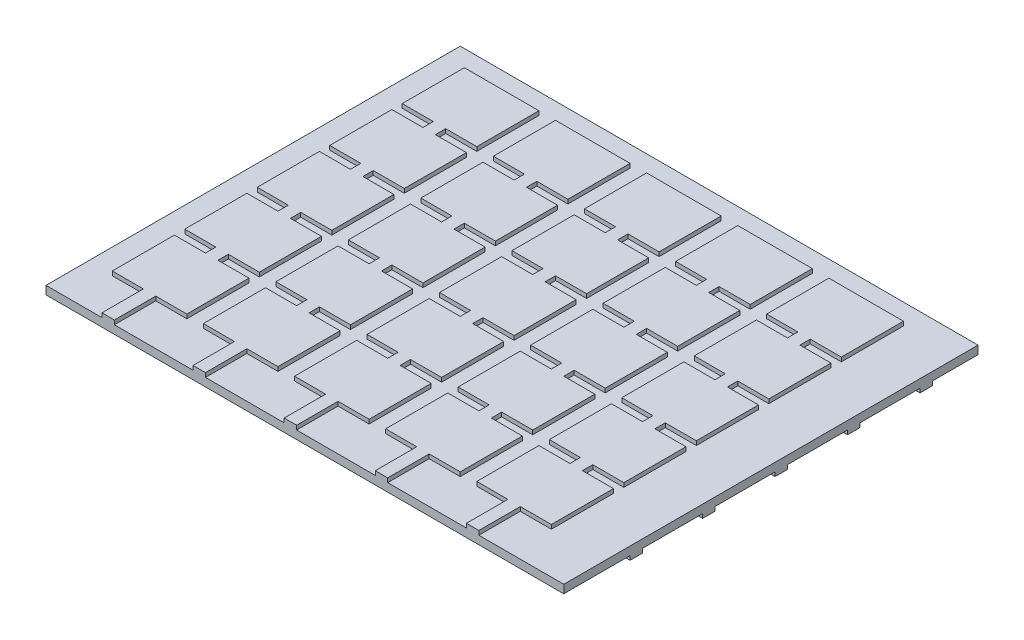
SolidWorks part; units mm, degrees
ref_plane "Front Plane" through (0, 0, 0) normal (0, 0, 1) x (1, 0, 0)
ref_plane "Top Plane" through (0, 0, 0) normal (0, 1, 0) x (1, 0, 0)
ref_plane "Right Plane" through (0, 0, 0) normal (1, 0, 0) x (0, 0, -1)
sketch "Sketch1" plane through (0, 0, 0) normal (0, 1, 0) x (1, 0, 0)
  line L1 (-62.5, 50) -> (62.5, 50)
  line L2 (-62.5, 50) -> (-62.5, -50)
  line L3 (-62.5, -50) -> (62.5, -50)
  line L4 (62.5, 50) -> (62.5, -50)
  dimension "D1" = 100
  dimension "D2" = 125
  dimension "D3" = 62.5
  dimension "D4" = 50
extrude "Boss-Extrude1" add sketch "Sketch1" along normal blind 2
sketch "Sketch2" plane through (0, 2, 0) normal (0, 1, 0) x (1, 0, 0)
  line L0 (62.5, 50) -> (-62.5, 50) construction
  line L1 (-56.5, 45) -> (-38.5, 45)
  line L2 (-56.5, 45) -> (-56.5, 30)
  line L3 (-56.5, 30) -> (-49, 30)
  line L4 (-38.5, 45) -> (-38.5, 30)
  line L5 (-62.5, 50) -> (-62.5, -50) construction
  line L6 (-34.5, 45) -> (-34.5, 30)
  line L7 (-34.5, 45) -> (-16.5, 45)
  line L8 (-16.5, 45) -> (-16.5, 30)
  line L9 (-34.5, 30) -> (-27, 30)
  line L10 (-12.5, 45) -> (-12.5, 30)
  line L11 (-12.5, 45) -> (5.5, 45)
  line L12 (5.5, 45) -> (5.5, 30)
  line L13 (-12.5, 30) -> (-5, 30)
  line L14 (9.5, 45) -> (9.5, 30)
  line L15 (9.5, 45) -> (27.5, 45)
  line L16 (27.5, 45) -> (27.5, 30)
  line L17 (9.5, 30) -> (17, 30)
  line L18 (31.5, 45) -> (31.5, 30)
  line L19 (31.5, 45) -> (49.5, 45)
  line L20 (49.5, 45) -> (49.5, 30)
  line L21 (31.5, 30) -> (39, 30)
  line L22 (-34.5, 27.5) -> (-34.5, 12.5)
  line L23 (-34.5, 27.5) -> (-27, 27.5)
  line L24 (-16.5, 27.5) -> (-16.5, 12.5)
  line L25 (-34.5, 12.5) -> (-27, 12.5)
  line L26 (-12.5, 27.5) -> (-12.5, 12.5)
  line L27 (-12.5, 27.5) -> (-5, 27.5)
  line L28 (5.5, 27.5) -> (5.5, 12.5)
  line L29 (-12.5, 12.5) -> (-5, 12.5)
  line L30 (9.5, 27.5) -> (9.5, 12.5)
  line L31 (9.5, 27.5) -> (17, 27.5)
  line L32 (27.5, 27.5) -> (27.5, 12.5)
  line L33 (9.5, 12.5) -> (17, 12.5)
  line L34 (31.5, 27.5) -> (31.5, 12.5)
  line L35 (31.5, 27.5) -> (39, 27.5)
  line L36 (49.5, 27.5) -> (49.5, 12.5)
  line L37 (31.5, 12.5) -> (39, 12.5)
  line L38 (-34.5, 10) -> (-34.5, -5)
  line L39 (-34.5, 10) -> (-27, 10)
  line L40 (-16.5, 10) -> (-16.5, -5)
  line L41 (-34.5, -5) -> (-27, -5)
  line L42 (-12.5, 10) -> (-12.5, -5)
  line L43 (-12.5, 10) -> (-5, 10)
  line L44 (5.5, 10) -> (5.5, -5)
  line L45 (-12.5, -5) -> (-5, -5)
  line L46 (9.5, 10) -> (9.5, -5)
  line L47 (9.5, 10) -> (17, 10)
  line L48 (27.5, 10) -> (27.5, -5)
  line L49 (9.5, -5) -> (17, -5)
  line L50 (31.5, 10) -> (31.5, -5)
  line L51 (31.5, 10) -> (39, 10)
  line L52 (49.5, 10) -> (49.5, -5)
  line L53 (31.5, -5) -> (39, -5)
  line L54 (-34.5, -7.5) -> (-34.5, -22.5)
  line L55 (-34.5, -7.5) -> (-27, -7.5)
  line L56 (-16.5, -7.5) -> (-16.5, -22.5)
  line L57 (-34.5, -22.5) -> (-27, -22.5)
  line L58 (-12.5, -7.5) -> (-12.5, -22.5)
  line L59 (-12.5, -7.5) -> (-5, -7.5)
  line L60 (5.5, -7.5) -> (5.5, -22.5)
  line L61 (-12.5, -22.5) -> (-5, -22.5)
  line L62 (9.5, -7.5) -> (9.5, -22.5)
  line L63 (9.5, -7.5) -> (17, -7.5)
  line L64 (27.5, -7.5) -> (27.5, -22.5)
  line L65 (9.5, -22.5) -> (17, -22.5)
  line L66 (31.5, -7.5) -> (31.5, -22.5)
  line L67 (31.5, -7.5) -> (39, -7.5)
  line L68 (49.5, -7.5) -> (49.5, -22.5)
  line L69 (31.5, -22.5) -> (39, -22.5)
  line L70 (-34.5, -25) -> (-34.5, -40)
  line L71 (-34.5, -25) -> (-27, -25)
  line L72 (-16.5, -25) -> (-16.5, -40)
  line L73 (-34.5, -40) -> (-27, -40)
  line L74 (-12.5, -25) -> (-12.5, -40)
  line L75 (-12.5, -25) -> (-5, -25)
  line L76 (5.5, -25) -> (5.5, -40)
  line L77 (-12.5, -40) -> (-5, -40)
  line L78 (9.5, -25) -> (9.5, -40)
  line L79 (9.5, -25) -> (17, -25)
  line L80 (27.5, -25) -> (27.5, -40)
  line L81 (9.5, -40) -> (17, -40)
  line L82 (31.5, -25) -> (31.5, -40)
  line L83 (31.5, -25) -> (39, -25)
  line L84 (49.5, -25) -> (49.5, -40)
  line L85 (31.5, -40) -> (39, -40)
  line L86 (-56.5, 27.5) -> (-56.5, 12.5)
  line L87 (-56.5, 27.5) -> (-49, 27.5)
  line L88 (-38.5, 27.5) -> (-38.5, 12.5)
  line L89 (-56.5, 12.5) -> (-49, 12.5)
  line L90 (-56.5, 10) -> (-56.5, -5)
  line L91 (-56.5, 10) -> (-49, 10)
  line L92 (-38.5, 10) -> (-38.5, -5)
  line L93 (-56.5, -5) -> (-49, -5)
  line L94 (-56.5, -7.5) -> (-56.5, -22.5)
  line L95 (-56.5, -7.5) -> (-49, -7.5)
  line L96 (-38.5, -7.5) -> (-38.5, -22.5)
  line L97 (-56.5, -22.5) -> (-49, -22.5)
  line L98 (-56.5, -25) -> (-56.5, -40)
  line L99 (-56.5, -25) -> (-49, -25)
  line L100 (-38.5, -25) -> (-38.5, -40)
  line L101 (-56.5, -40) -> (-49, -40)
  line L102 (-62.5, -50) -> (62.5, -50) construction
  line L103 (-46, 30) -> (-38.5, 30)
  line L104 (-49, 30) -> (-49, 27.5)
  line L105 (-49, -50) -> (-46, -50)
  line L106 (-46, 30) -> (-46, 27.5)
  line L107 (-46, 27.5) -> (-38.5, 27.5)
  line L108 (-24, 30) -> (-16.5, 30)
  line L109 (-27, 30) -> (-27, 27.5)
  line L110 (-27, -50) -> (-24, -50)
  line L111 (-24, 30) -> (-24, 27.5)
  line L112 (-2, 30) -> (5.5, 30)
  line L113 (-5, 30) -> (-5, 27.5)
  line L114 (-5, -50) -> (-2, -50)
  line L115 (-2, 30) -> (-2, 27.5)
  line L116 (42, 30) -> (49.5, 30)
  line L117 (17, 30) -> (17, 27.5)
  line L118 (17, -50) -> (20, -50)
  line L119 (20, 30) -> (20, 27.5)
  line L121 (39, 30) -> (39, 27.5)
  line L122 (39, -50) -> (42, -50)
  line L123 (42, 30) -> (42, 27.5)
  line L124 (-46, 12.5) -> (-46, 10)
  line L125 (-49, 12.5) -> (-49, 10)
  line L126 (-46, 12.5) -> (-38.5, 12.5)
  line L127 (-46, 10) -> (-38.5, 10)
  line L128 (-49, -5) -> (-49, -7.5)
  line L129 (-46, -5) -> (-46, -7.5)
  line L130 (-46, -5) -> (-38.5, -5)
  line L131 (-46, -7.5) -> (-38.5, -7.5)
  line L132 (-49, -22.5) -> (-49, -25)
  line L133 (-46, -22.5) -> (-46, -25)
  line L134 (-46, -22.5) -> (-38.5, -22.5)
  line L135 (-46, -25) -> (-38.5, -25)
  line L136 (-49, -40) -> (-49, -50)
  line L137 (-46, -40) -> (-46, -50)
  line L138 (-46, -40) -> (-38.5, -40)
  line L139 (-24, -40) -> (-24, -50)
  line L140 (-27, -40) -> (-27, -50)
  line L141 (-24, -40) -> (-16.5, -40)
  line L142 (-24, -25) -> (-16.5, -25)
  line L143 (-24, -22.5) -> (-16.5, -22.5)
  line L144 (-24, -22.5) -> (-24, -25)
  line L145 (-27, -22.5) -> (-27, -25)
  line L146 (-24, -5) -> (-24, -7.5)
  line L147 (-27, -5) -> (-27, -7.5)
  line L148 (-24, -5) -> (-16.5, -5)
  line L149 (-24, -7.5) -> (-16.5, -7.5)
  line L150 (-24, 10) -> (-16.5, 10)
  line L151 (-24, 12.5) -> (-16.5, 12.5)
  line L152 (-27, 12.5) -> (-27, 10)
  line L153 (-24, 12.5) -> (-24, 10)
  line L154 (-24, 27.5) -> (-16.5, 27.5)
  line L155 (-2, 27.5) -> (5.5, 27.5)
  line L156 (-5, 12.5) -> (-5, 10)
  line L157 (-2, 12.5) -> (-2, 10)
  line L158 (-2, 12.5) -> (5.5, 12.5)
  line L159 (-2, 10) -> (5.5, 10)
  line L160 (-5, -5) -> (-5, -7.5)
  line L161 (-2, -5) -> (-2, -7.5)
  line L162 (-2, -5) -> (5.5, -5)
  line L163 (-2, -7.5) -> (5.5, -7.5)
  line L164 (-5, -22.5) -> (-5, -25)
  line L165 (-2, -22.5) -> (-2, -25)
  line L166 (-2, -22.5) -> (5.5, -22.5)
  line L167 (-2, -25) -> (5.5, -25)
  line L168 (-5, -40) -> (-5, -50)
  line L169 (-2, -40) -> (-2, -50)
  line L170 (-2, -40) -> (5.5, -40)
  line L171 (20, -40) -> (20, -50)
  line L172 (17, -40) -> (17, -50)
  line L173 (20, -40) -> (27.5, -40)
  line L174 (20, -22.5) -> (20, -25)
  line L175 (17, -22.5) -> (17, -25)
  line L176 (20, -22.5) -> (27.5, -22.5)
  line L177 (20, -25) -> (27.5, -25)
  line L178 (20, -5) -> (20, -7.5)
  line L179 (17, -5) -> (17, -7.5)
  line L180 (20, -5) -> (27.5, -5)
  line L181 (20, -7.5) -> (27.5, -7.5)
  line L182 (20, 12.5) -> (20, 10)
  line L183 (17, 12.5) -> (17, 10)
  line L184 (20, 12.5) -> (27.5, 12.5)
  line L185 (20, 10) -> (27.5, 10)
  line L186 (20, 30) -> (27.5, 30)
  line L187 (20, 27.5) -> (27.5, 27.5)
  line L188 (42, 27.5) -> (49.5, 27.5)
  line L189 (42, 12.5) -> (42, 10)
  line L190 (39, 12.5) -> (39, 10)
  line L191 (42, 12.5) -> (49.5, 12.5)
  line L192 (42, 10) -> (49.5, 10)
  line L193 (39, -5) -> (39, -7.5)
  line L194 (42, -5) -> (42, -7.5)
  line L195 (42, -5) -> (49.5, -5)
  line L196 (42, -7.5) -> (49.5, -7.5)
  line L197 (39, -22.5) -> (39, -25)
  line L198 (42, -22.5) -> (42, -25)
  line L199 (42, -22.5) -> (49.5, -22.5)
  line L200 (42, -25) -> (49.5, -25)
  line L201 (39, -40) -> (39, -50)
  line L202 (42, -40) -> (42, -50)
  line L203 (42, -40) -> (49.5, -40)
  dimension "D1" = 5
  dimension "D2" = 6
  dimension "D3" = 18
  dimension "D4" = 15
  dimension "D8" = 7.5
  dimension "D9" = 7.5
  dimension "D10" = 22
  dimension "D12" = 7.5
  dimension "D14" = 7.5
  dimension "D16" = 7.5
  dimension "D5" = 5
  dimension "D6" = 5
extrude "Boss-Extrude2" add sketch "Sketch2" along normal blind 1
sketch "Sketch3" plane through (0, 0, 0) normal (0, -1, 0) x (1, 0, 0)
  line L0 (-38.5, 40) -> (-38.5, 34)
  line L1 (-56.5, 40) -> (-38.5, 40)
  line L2 (-56.5, 40) -> (-56.5, 25)
  line L3 (-56.5, -45) -> (-38.5, -45)
  line L4 (49.5, 40) -> (49.5, 34)
  line L5 (-34.5, 40) -> (-34.5, 34)
  line L6 (-16.5, 40) -> (-16.5, 34)
  line L7 (9.5, 40) -> (9.5, 34)
  line L8 (-12.5, 40) -> (-12.5, 34)
  line L9 (5.5, 40) -> (5.5, 34)
  line L10 (27.5, 40) -> (27.5, 34)
  line L11 (31.5, 40) -> (31.5, 34)
  line L12 (-56.5, 25) -> (-38.5, 25)
  line L13 (-56.5, 22.5) -> (-38.5, 22.5)
  line L14 (49.5, 7.5) -> (31.5, 7.5)
  line L15 (-56.5, 5) -> (-38.5, 5)
  line L16 (-56.5, -10) -> (-38.5, -10)
  line L17 (49.5, -12.5) -> (31.5, -12.5)
  line L18 (-56.5, -27.5) -> (-38.5, -27.5)
  line L19 (49.5, -30) -> (31.5, -30)
  line L20 (-56.5, -30) -> (-56.5, -45)
  line L21 (-38.5, -30) -> (-38.5, -36)
  line L22 (-34.5, -30) -> (-34.5, -36)
  line L23 (-34.5, -27.5) -> (-16.5, -27.5)
  line L24 (-38.5, -30) -> (-56.5, -30)
  line L25 (-12.5, -27.5) -> (5.5, -27.5)
  line L26 (-16.5, -30) -> (-34.5, -30)
  line L27 (-16.5, -30) -> (-16.5, -36)
  line L28 (-12.5, -30) -> (-12.5, -36)
  line L29 (9.5, -27.5) -> (27.5, -27.5)
  line L30 (5.5, -30) -> (-12.5, -30)
  line L31 (9.5, -30) -> (9.5, -36)
  line L32 (5.5, -30) -> (5.5, -36)
  line L33 (27.5, -30) -> (27.5, -36)
  line L34 (31.5, -30) -> (31.5, -36)
  line L35 (31.5, -27.5) -> (49.5, -27.5)
  line L36 (27.5, -30) -> (9.5, -30)
  line L37 (49.5, -30) -> (49.5, -36)
  line L38 (31.5, -10) -> (49.5, -10)
  line L39 (27.5, -12.5) -> (9.5, -12.5)
  line L40 (27.5, -12.5) -> (27.5, -18.5)
  line L41 (31.5, -12.5) -> (31.5, -18.5)
  line L42 (49.5, -12.5) -> (49.5, -18.5)
  line L43 (49.5, 5) -> (49.5, -1)
  line L44 (31.5, 5) -> (31.5, -1)
  line L45 (27.5, 5) -> (27.5, -1)
  line L46 (27.5, 7.5) -> (9.5, 7.5)
  line L47 (31.5, 5) -> (49.5, 5)
  line L48 (31.5, 22.5) -> (49.5, 22.5)
  line L49 (31.5, 25) -> (49.5, 25)
  line L50 (27.5, 22.5) -> (27.5, 16.5)
  line L51 (31.5, 22.5) -> (31.5, 16.5)
  line L52 (49.5, 22.5) -> (49.5, 16.5)
  line L53 (31.5, 40) -> (49.5, 40)
  line L54 (9.5, 40) -> (27.5, 40)
  line L55 (9.5, 25) -> (27.5, 25)
  line L56 (9.5, 22.5) -> (27.5, 22.5)
  line L57 (5.5, 22.5) -> (5.5, 16.5)
  line L58 (9.5, 22.5) -> (9.5, 16.5)
  line L59 (5.5, 7.5) -> (-12.5, 7.5)
  line L60 (9.5, 5) -> (27.5, 5)
  line L61 (5.5, 5) -> (5.5, -1)
  line L62 (9.5, 5) -> (9.5, -1)
  line L63 (9.5, -10) -> (27.5, -10)
  line L64 (5.5, -12.5) -> (-12.5, -12.5)
  line L65 (5.5, -12.5) -> (5.5, -18.5)
  line L66 (9.5, -12.5) -> (9.5, -18.5)
  line L67 (-12.5, -10) -> (5.5, -10)
  line L68 (-16.5, -12.5) -> (-34.5, -12.5)
  line L69 (-16.5, -12.5) -> (-16.5, -18.5)
  line L70 (-12.5, -12.5) -> (-12.5, -18.5)
  line L71 (-16.5, 7.5) -> (-34.5, 7.5)
  line L72 (-12.5, 5) -> (5.5, 5)
  line L73 (-16.5, 5) -> (-16.5, -1)
  line L74 (-12.5, 5) -> (-12.5, -1)
  line L75 (-12.5, 25) -> (5.5, 25)
  line L76 (-12.5, 22.5) -> (5.5, 22.5)
  line L77 (-16.5, 22.5) -> (-16.5, 16.5)
  line L78 (-12.5, 22.5) -> (-12.5, 16.5)
  line L79 (-12.5, 40) -> (5.5, 40)
  line L80 (-34.5, 40) -> (-16.5, 40)
  line L81 (-34.5, 25) -> (-16.5, 25)
  line L82 (-34.5, 22.5) -> (-16.5, 22.5)
  line L83 (-38.5, 22.5) -> (-38.5, 16.5)
  line L84 (-34.5, 22.5) -> (-34.5, 16.5)
  line L85 (-38.5, 7.5) -> (-56.5, 7.5)
  line L86 (-34.5, 5) -> (-16.5, 5)
  line L87 (-38.5, 5) -> (-38.5, -1)
  line L88 (-34.5, 5) -> (-34.5, -1)
  line L89 (-34.5, -10) -> (-16.5, -10)
  line L90 (-38.5, -12.5) -> (-56.5, -12.5)
  line L91 (-38.5, -12.5) -> (-38.5, -18.5)
  line L92 (-34.5, -12.5) -> (-34.5, -18.5)
  line L93 (-56.5, 22.5) -> (-56.5, 7.5)
  line L94 (-56.5, 5) -> (-56.5, -10)
  line L95 (-56.5, -12.5) -> (-56.5, -27.5)
  line L96 (-34.5, -45) -> (-16.5, -45)
  line L97 (-12.5, -45) -> (5.5, -45)
  line L98 (9.5, -45) -> (27.5, -45)
  line L99 (31.5, -45) -> (49.5, -45)
  line L100 (62.5, 50) -> (62.5, -50) construction
  line L101 (-38.5, -39) -> (-34.5, -39)
  line L102 (-38.5, -39) -> (-38.5, -45)
  line L103 (-38.5, -36) -> (-34.5, -36)
  line L104 (62.5, -39) -> (62.5, -36)
  line L105 (-38.5, 31) -> (-38.5, 25)
  line L106 (-38.5, -21.5) -> (-34.5, -21.5)
  line L107 (-38.5, -21.5) -> (-38.5, -27.5)
  line L108 (-38.5, -18.5) -> (-34.5, -18.5)
  line L109 (62.5, -21.5) -> (62.5, -18.5)
  line L110 (-38.5, -4) -> (-34.5, -4)
  line L111 (-38.5, -4) -> (-38.5, -10)
  line L112 (-38.5, -1) -> (-34.5, -1)
  line L113 (62.5, -4) -> (62.5, -1)
  line L114 (-38.5, 13.5) -> (-34.5, 13.5)
  line L115 (-38.5, 13.5) -> (-38.5, 7.5)
  line L116 (-38.5, 16.5) -> (-34.5, 16.5)
  line L117 (62.5, 13.5) -> (62.5, 16.5)
  line L118 (-38.5, 31) -> (-34.5, 31)
  line L119 (-34.5, 31) -> (-34.5, 25)
  line L120 (-38.5, 34) -> (-34.5, 34)
  line L121 (62.5, 31) -> (62.5, 34)
  line L122 (-16.5, 34) -> (-12.5, 34)
  line L123 (-16.5, 31) -> (-12.5, 31)
  line L124 (-16.5, 31) -> (-16.5, 25)
  line L125 (-12.5, 31) -> (-12.5, 25)
  line L126 (5.5, 34) -> (9.5, 34)
  line L127 (5.5, 31) -> (9.5, 31)
  line L128 (5.5, 31) -> (5.5, 25)
  line L129 (9.5, 31) -> (9.5, 25)
  line L130 (27.5, 34) -> (31.5, 34)
  line L131 (27.5, 31) -> (31.5, 31)
  line L132 (27.5, 31) -> (27.5, 25)
  line L133 (31.5, 31) -> (31.5, 25)
  line L134 (49.5, 34) -> (62.5, 34)
  line L135 (49.5, 31) -> (62.5, 31)
  line L136 (49.5, 31) -> (49.5, 25)
  line L137 (-34.5, 13.5) -> (-34.5, 7.5)
  line L138 (-16.5, 16.5) -> (-12.5, 16.5)
  line L139 (-16.5, 13.5) -> (-12.5, 13.5)
  line L140 (-16.5, 13.5) -> (-16.5, 7.5)
  line L141 (-12.5, 13.5) -> (-12.5, 7.5)
  line L142 (5.5, 16.5) -> (9.5, 16.5)
  line L143 (5.5, 13.5) -> (9.5, 13.5)
  line L144 (5.5, 13.5) -> (5.5, 7.5)
  line L145 (9.5, 13.5) -> (9.5, 7.5)
  line L146 (27.5, 16.5) -> (31.5, 16.5)
  line L147 (27.5, 13.5) -> (31.5, 13.5)
  line L148 (27.5, 13.5) -> (27.5, 7.5)
  line L149 (31.5, 13.5) -> (31.5, 7.5)
  line L150 (49.5, 16.5) -> (62.5, 16.5)
  line L151 (49.5, 13.5) -> (62.5, 13.5)
  line L152 (49.5, 13.5) -> (49.5, 7.5)
  line L153 (49.5, -4) -> (49.5, -10)
  line L154 (49.5, -1) -> (62.5, -1)
  line L155 (49.5, -4) -> (62.5, -4)
  line L156 (31.5, -4) -> (31.5, -10)
  line L157 (27.5, -4) -> (27.5, -10)
  line L158 (27.5, -1) -> (31.5, -1)
  line L159 (27.5, -4) -> (31.5, -4)
  line L160 (9.5, -4) -> (9.5, -10)
  line L161 (5.5, -4) -> (5.5, -10)
  line L162 (5.5, -1) -> (9.5, -1)
  line L163 (5.5, -4) -> (9.5, -4)
  line L164 (-12.5, -4) -> (-12.5, -10)
  line L165 (-16.5, -4) -> (-16.5, -10)
  line L166 (-16.5, -1) -> (-12.5, -1)
  line L167 (-16.5, -4) -> (-12.5, -4)
  line L168 (-34.5, -4) -> (-34.5, -10)
  line L169 (-34.5, -21.5) -> (-34.5, -27.5)
  line L170 (-16.5, -18.5) -> (-12.5, -18.5)
  line L171 (-16.5, -21.5) -> (-12.5, -21.5)
  line L172 (-16.5, -21.5) -> (-16.5, -27.5)
  line L173 (-12.5, -21.5) -> (-12.5, -27.5)
  line L174 (5.5, -18.5) -> (9.5, -18.5)
  line L175 (5.5, -21.5) -> (9.5, -21.5)
  line L176 (5.5, -21.5) -> (5.5, -27.5)
  line L177 (9.5, -21.5) -> (9.5, -27.5)
  line L178 (27.5, -18.5) -> (31.5, -18.5)
  line L179 (27.5, -21.5) -> (31.5, -21.5)
  line L180 (49.5, -18.5) -> (62.5, -18.5)
  line L181 (49.5, -21.5) -> (62.5, -21.5)
  line L182 (31.5, -21.5) -> (31.5, -27.5)
  line L183 (27.5, -21.5) -> (27.5, -27.5)
  line L184 (49.5, -21.5) -> (49.5, -27.5)
  line L185 (49.5, -39) -> (49.5, -45)
  line L186 (49.5, -36) -> (62.5, -36)
  line L187 (49.5, -39) -> (62.5, -39)
  line L188 (31.5, -39) -> (31.5, -45)
  line L189 (27.5, -39) -> (27.5, -45)
  line L190 (27.5, -36) -> (31.5, -36)
  line L191 (27.5, -39) -> (31.5, -39)
  line L192 (9.5, -39) -> (9.5, -45)
  line L193 (5.5, -39) -> (5.5, -45)
  line L194 (5.5, -36) -> (9.5, -36)
  line L195 (5.5, -39) -> (9.5, -39)
  line L196 (-12.5, -39) -> (-12.5, -45)
  line L197 (-16.5, -39) -> (-16.5, -45)
  line L198 (-16.5, -36) -> (-12.5, -36)
  line L199 (-16.5, -39) -> (-12.5, -39)
  line L200 (-34.5, -39) -> (-34.5, -45)
  dimension "D1" = 6
  dimension "D3" = 6
  dimension "D5" = 6
  dimension "D7" = 6
  dimension "D9" = 6
extrude "Boss-Extrude3" add sketch "Sketch3" along normal blind 1
